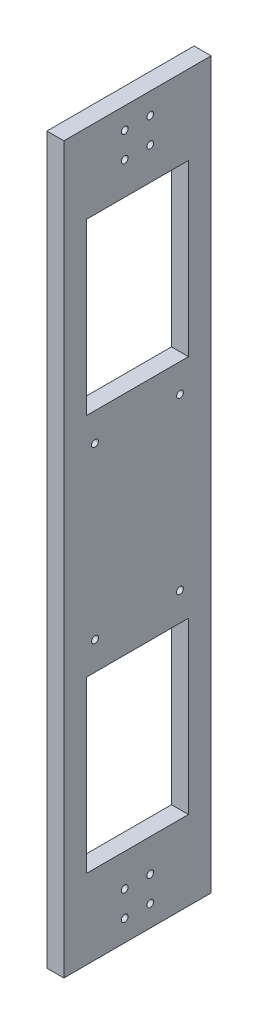
SolidWorks part; units mm, degrees
material "ABS"
ref_plane "Front Plane" through (0, 0, 0) normal (0, 0, 1) x (1, 0, 0)
ref_plane "Top Plane" through (0, 0, 0) normal (0, 1, 0) x (1, 0, 0)
ref_plane "Right Plane" through (0, 0, 0) normal (1, 0, 0) x (0, 0, -1)
ref_plane "P_yoke_184_x" through (-157.1, 0, 0) normal (1, 0, 0) x (0, 0, -1)
sketch "Sketch1" plane through (-157.1, 0, 0) normal (1, 0, 0) x (0, 0, -1)
  line L1 (-26, -128) -> (26, -128)
  line L2 (-26, -128) -> (-26, 128)
  line L3 (-26, 128) -> (26, 128)
  line L4 (26, -128) -> (26, 128)
extrude "Boss-Extrude1" add sketch "Sketch1" along normal blind 6
hole_wizard "M2 Clearance Hole1" positions "Sketch3" profile "Sketch2" hole size "M2" standard "ISO"
sketch "Sketch3" plane through (-157.1, 0, 0) normal (-1, 0, 0) x (0, 0, 1)
  point P0 (-4.5, 111.5)
sketch "Sketch2" plane through (-157.1, 111.5, -4.5) normal (0, 1, 0) x (0, 0, 1)
  line L0 (0, 0) -> (0, 6)
  line L1 (0, 6) -> (1.2, 6)
  line L2 (1.2, 6) -> (1.2, 0)
  line L5 (1.2, 0) -> (0, 0)
  line L11 (0, -6.35) -> (0, 107.95) construction
  dimension "Thru Hole Dia." = 2.4
  dimension "Thru Hole Depth" = 6
hole_wizard "M2 Clearance Hole2" positions "Sketch5" profile "Sketch4" hole size "M2" standard "ISO"
sketch "Sketch5" plane through (-157.1, 0, 0) normal (-1, 0, 0) x (0, 0, 1)
  point P0 (4.5, 111.5)
sketch "Sketch4" plane through (-157.1, 111.5, 4.5) normal (0, 1, 0) x (0, 0, 1)
  line L0 (0, 0) -> (0, 6)
  line L1 (0, 6) -> (1.2, 6)
  line L2 (1.2, 6) -> (1.2, 0)
  line L5 (1.2, 0) -> (0, 0)
  line L11 (0, -6.35) -> (0, 107.95) construction
  dimension "Thru Hole Dia." = 2.4
  dimension "Thru Hole Depth" = 6
hole_wizard "M2 Clearance Hole3" positions "Sketch7" profile "Sketch6" hole size "M2" standard "ISO"
sketch "Sketch7" plane through (-157.1, 0, 0) normal (-1, 0, 0) x (0, 0, 1)
  point P0 (-4.5, 120.5)
sketch "Sketch6" plane through (-157.1, 120.5, -4.5) normal (0, 1, 0) x (0, 0, 1)
  line L0 (0, 0) -> (0, 6)
  line L1 (0, 6) -> (1.2, 6)
  line L2 (1.2, 6) -> (1.2, 0)
  line L5 (1.2, 0) -> (0, 0)
  line L11 (0, -6.35) -> (0, 107.95) construction
  dimension "Thru Hole Dia." = 2.4
  dimension "Thru Hole Depth" = 6
hole_wizard "M2 Clearance Hole4" positions "Sketch9" profile "Sketch8" hole size "M2" standard "ISO"
sketch "Sketch9" plane through (-157.1, 0, 0) normal (-1, 0, 0) x (0, 0, 1)
  point P0 (4.5, 120.5)
sketch "Sketch8" plane through (-157.1, 120.5, 4.5) normal (0, 1, 0) x (0, 0, 1)
  line L0 (0, 0) -> (0, 6)
  line L1 (0, 6) -> (1.2, 6)
  line L2 (1.2, 6) -> (1.2, 0)
  line L5 (1.2, 0) -> (0, 0)
  line L11 (0, -6.35) -> (0, 107.95) construction
  dimension "Thru Hole Dia." = 2.4
  dimension "Thru Hole Depth" = 6
hole_wizard "M2 Clearance Hole5" positions "Sketch11" profile "Sketch10" hole size "M2" standard "ISO"
sketch "Sketch11" plane through (-157.1, 0, 0) normal (-1, 0, 0) x (0, 0, 1)
  point P0 (-4.5, -120.5)
sketch "Sketch10" plane through (-157.1, -120.5, -4.5) normal (0, 1, 0) x (0, 0, 1)
  line L0 (0, 0) -> (0, 6)
  line L1 (0, 6) -> (1.2, 6)
  line L2 (1.2, 6) -> (1.2, 0)
  line L5 (1.2, 0) -> (0, 0)
  line L11 (0, -6.35) -> (0, 107.95) construction
  dimension "Thru Hole Dia." = 2.4
  dimension "Thru Hole Depth" = 6
hole_wizard "M2 Clearance Hole6" positions "Sketch13" profile "Sketch12" hole size "M2" standard "ISO"
sketch "Sketch13" plane through (-157.1, 0, 0) normal (-1, 0, 0) x (0, 0, 1)
  point P0 (4.5, -120.5)
sketch "Sketch12" plane through (-157.1, -120.5, 4.5) normal (0, 1, 0) x (0, 0, 1)
  line L0 (0, 0) -> (0, 6)
  line L1 (0, 6) -> (1.2, 6)
  line L2 (1.2, 6) -> (1.2, 0)
  line L5 (1.2, 0) -> (0, 0)
  line L11 (0, -6.35) -> (0, 107.95) construction
  dimension "Thru Hole Dia." = 2.4
  dimension "Thru Hole Depth" = 6
hole_wizard "M2 Clearance Hole7" positions "Sketch15" profile "Sketch14" hole size "M2" standard "ISO"
sketch "Sketch15" plane through (-157.1, 0, 0) normal (-1, 0, 0) x (0, 0, 1)
  point P0 (-4.5, -111.5)
sketch "Sketch14" plane through (-157.1, -111.5, -4.5) normal (0, 1, 0) x (0, 0, 1)
  line L0 (0, 0) -> (0, 6)
  line L1 (0, 6) -> (1.2, 6)
  line L2 (1.2, 6) -> (1.2, 0)
  line L5 (1.2, 0) -> (0, 0)
  line L11 (0, -6.35) -> (0, 107.95) construction
  dimension "Thru Hole Dia." = 2.4
  dimension "Thru Hole Depth" = 6
hole_wizard "M2 Clearance Hole8" positions "Sketch17" profile "Sketch16" hole size "M2" standard "ISO"
sketch "Sketch17" plane through (-157.1, 0, 0) normal (-1, 0, 0) x (0, 0, 1)
  point P0 (4.5, -111.5)
sketch "Sketch16" plane through (-157.1, -111.5, 4.5) normal (0, 1, 0) x (0, 0, 1)
  line L0 (0, 0) -> (0, 6)
  line L1 (0, 6) -> (1.2, 6)
  line L2 (1.2, 6) -> (1.2, 0)
  line L5 (1.2, 0) -> (0, 0)
  line L11 (0, -6.35) -> (0, 107.95) construction
  dimension "Thru Hole Dia." = 2.4
  dimension "Thru Hole Depth" = 6
hole_wizard "M2 Clearance Hole9" positions "Sketch19" profile "Sketch18" hole size "M2" standard "ISO"
sketch "Sketch19" plane through (-157.1, 0, 0) normal (-1, 0, 0) x (0, 0, 1)
  point P0 (-15, -30)
sketch "Sketch18" plane through (-157.1, -30, -15) normal (0, 1, 0) x (0, 0, 1)
  line L0 (0, 0) -> (0, 6)
  line L1 (0, 6) -> (1.2, 6)
  line L2 (1.2, 6) -> (1.2, 0)
  line L5 (1.2, 0) -> (0, 0)
  line L11 (0, -6.35) -> (0, 107.95) construction
  dimension "Thru Hole Dia." = 2.4
  dimension "Thru Hole Depth" = 6
hole_wizard "M2 Clearance Hole10" positions "Sketch21" profile "Sketch20" hole size "M2" standard "ISO"
sketch "Sketch21" plane through (-157.1, 0, 0) normal (-1, 0, 0) x (0, 0, 1)
  point P0 (15, -30)
sketch "Sketch20" plane through (-157.1, -30, 15) normal (0, 1, 0) x (0, 0, 1)
  line L0 (0, 0) -> (0, 6)
  line L1 (0, 6) -> (1.2, 6)
  line L2 (1.2, 6) -> (1.2, 0)
  line L5 (1.2, 0) -> (0, 0)
  line L11 (0, -6.35) -> (0, 107.95) construction
  dimension "Thru Hole Dia." = 2.4
  dimension "Thru Hole Depth" = 6
hole_wizard "M2 Clearance Hole11" positions "Sketch23" profile "Sketch22" hole size "M2" standard "ISO"
sketch "Sketch23" plane through (-157.1, 0, 0) normal (-1, 0, 0) x (0, 0, 1)
  point P0 (-15, 30)
sketch "Sketch22" plane through (-157.1, 30, -15) normal (0, 1, 0) x (0, 0, 1)
  line L0 (0, 0) -> (0, 6)
  line L1 (0, 6) -> (1.2, 6)
  line L2 (1.2, 6) -> (1.2, 0)
  line L5 (1.2, 0) -> (0, 0)
  line L11 (0, -6.35) -> (0, 107.95) construction
  dimension "Thru Hole Dia." = 2.4
  dimension "Thru Hole Depth" = 6
hole_wizard "M2 Clearance Hole12" positions "Sketch25" profile "Sketch24" hole size "M2" standard "ISO"
sketch "Sketch25" plane through (-157.1, 0, 0) normal (-1, 0, 0) x (0, 0, 1)
  point P0 (15, 30)
sketch "Sketch24" plane through (-157.1, 30, 15) normal (0, 1, 0) x (0, 0, 1)
  line L0 (0, 0) -> (0, 6)
  line L1 (0, 6) -> (1.2, 6)
  line L2 (1.2, 6) -> (1.2, 0)
  line L5 (1.2, 0) -> (0, 0)
  line L11 (0, -6.35) -> (0, 107.95) construction
  dimension "Thru Hole Dia." = 2.4
  dimension "Thru Hole Depth" = 6
ref_plane "P_winp1" through (-157.1, 0, 0) normal (1, 0, 0) x (0, 0, -1)
sketch "Sketch26" plane through (-157.1, 0, 0) normal (1, 0, 0) x (0, 0, -1)
  line L1 (-18, 40) -> (18, 40)
  line L2 (-18, 40) -> (-18, 100)
  line L3 (-18, 100) -> (18, 100)
  line L4 (18, 40) -> (18, 100)
extrude "Cut-Extrude2" cut sketch "Sketch26" along normal blind 6
ref_plane "P_winm1" through (-157.1, 0, 0) normal (1, 0, 0) x (0, 0, -1)
sketch "Sketch27" plane through (-157.1, 0, 0) normal (1, 0, 0) x (0, 0, -1)
  line L1 (-18, -100) -> (18, -100)
  line L2 (-18, -100) -> (-18, -40)
  line L3 (-18, -40) -> (18, -40)
  line L4 (18, -100) -> (18, -40)
extrude "Cut-Extrude4" cut sketch "Sketch27" along normal blind 6
